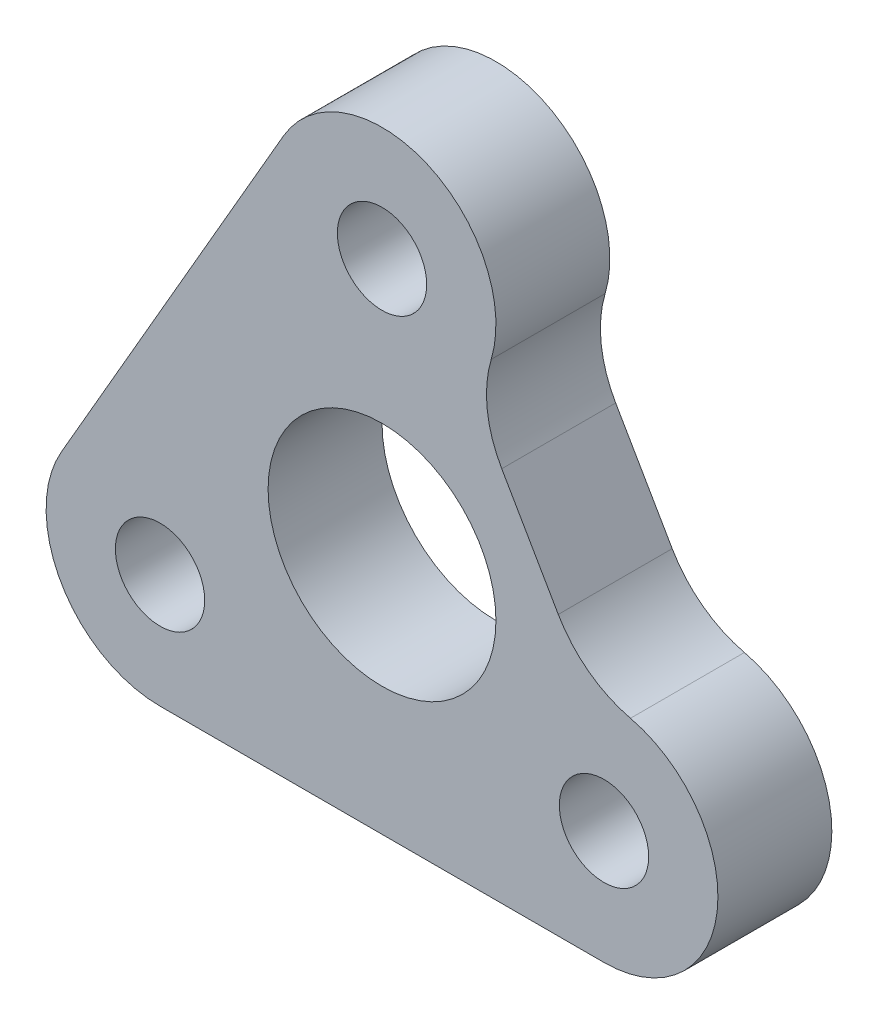
SolidWorks part; units mm, degrees
material "6061-T6 (SS)"
ref_plane "Front Plane" through (0, 0, 0) normal (0, 0, 1) x (1, 0, 0)
ref_plane "Top Plane" through (0, 0, 0) normal (0, 1, 0) x (1, 0, 0)
ref_plane "Right Plane" through (0, 0, 0) normal (1, 0, 0) x (0, 0, -1)
sketch "Sketch1" plane through (0, 0, 0) normal (0, 0, 1) x (1, 0, 0)
  line L3 (0, 14.2875) -> (12.3733, -7.1438) construction
  line L4 (12.3733, -7.1438) -> (-12.3733, -7.1438) construction
  line L5 (-12.3733, -7.1438) -> (0, 14.2875) construction
  line L6 (0, 26.9875) -> (23.3719, -13.4938)
  line L7 (23.3719, -13.4938) -> (-23.3719, -13.4938)
  line L8 (-23.3719, -13.4938) -> (0, 26.9875)
  circle A0 centre (0, 0) radius 6.35
  circle A1 centre (0, 14.2875) radius 2.4892
  circle A2 centre (12.3733, -7.1438) radius 2.4892
  circle A3 centre (-12.3733, -7.1438) radius 2.4892
  point P11 (0, 0)
  dimension "D1" = 12.7
  dimension "D2" = 4.9784
  dimension "D3" = 14.2875
  dimension "D5" = 6.35
  dimension "D4" = 3
extrude "Boss-Extrude1" add sketch "Sketch1" along normal blind 6.35
fillet "Fillet1" radius 6.35 3 edges at (23.3719, -13.4938, 3.175) (-23.3719, -13.4938, 3.175) (0, 26.9875, 3.175)
sketch "Sketch2" plane through (0, 0, 6.35) normal (0, 0, 1) x (1, 0, 0)
  line L0 (5.0055, 10.3802) -> (11.4923, -0.8552)
  line L1 (17.8726, -3.9687) -> (5.4993, 17.4625) construction
  circle A0 centre (0, 14.2875) radius 6.35
  circle A1 centre (12.3733, -7.1438) radius 6.35
  circle A2 centre (0, 0) radius 6.35 construction
  point P10 (11.2622, -0.8917)
  line M4 (17.8726, -3.9687) -> (5.4993, 17.4625)
  dimension "D1" = 12.7
  dimension "D2" = 9.525
extrude "Cut-Extrude1" cut sketch "Sketch2" against normal through all contours A1 A0 L0 M4
fillet "Fillet2" radius 6.35 2 edges at (11.4923, -0.8552, 3.175) (5.0055, 10.3802, 3.175)
